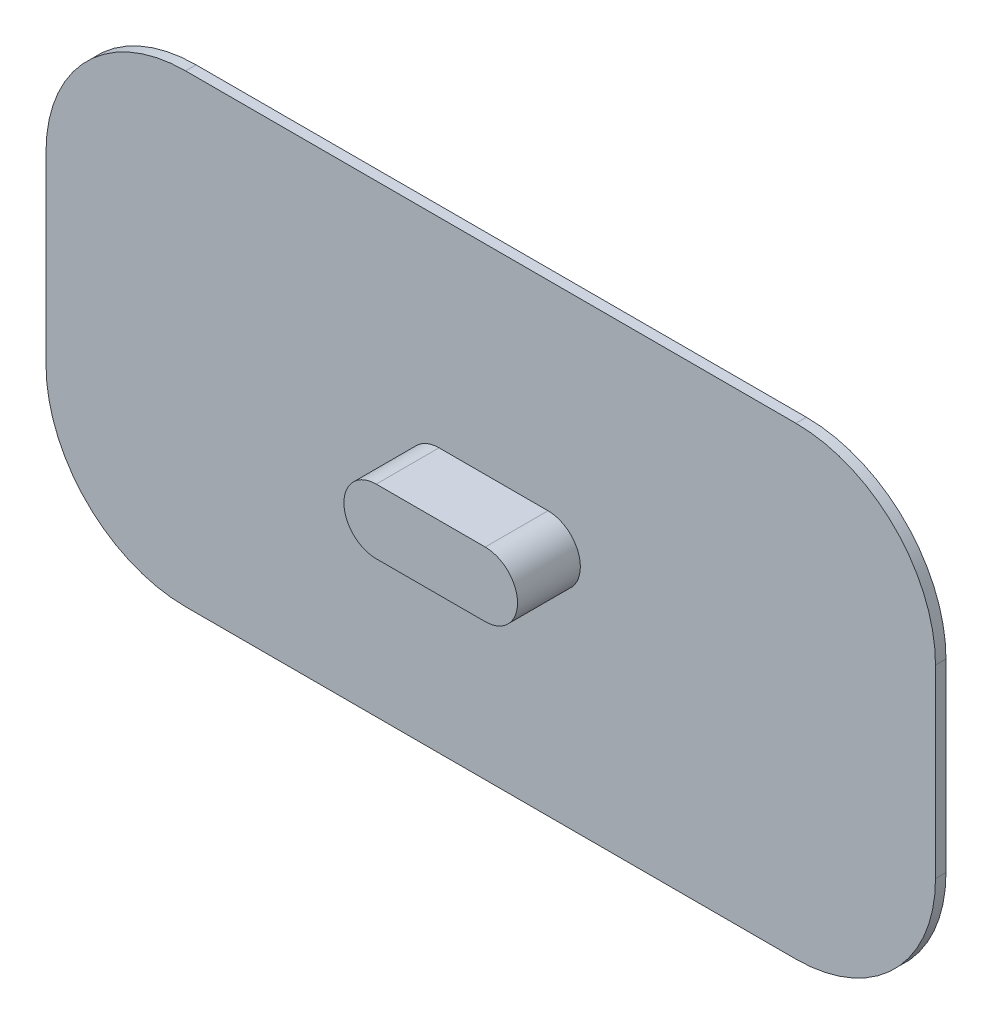
SolidWorks part; units mm, degrees
ref_plane "前视基准面" through (0, 0, 0) normal (0, 0, 1) x (1, 0, 0)
ref_plane "上视基准面" through (0, 0, 0) normal (0, 1, 0) x (1, 0, 0)
ref_plane "右视基准面" through (0, 0, 0) normal (1, 0, 0) x (0, 0, -1)
sketch "草图1" plane through (0, 0, 0) normal (0, 0, 1) x (1, 0, 0)
  line L8 (87.45, 66.5) -> (-87.45, 66.5)
  line L9 (-127.45, 26.5) -> (-127.45, -26.5)
  line L10 (-87.45, -66.5) -> (87.45, -66.5)
  line L11 (127.45, -26.5) -> (127.45, 26.5)
  arc A8 (-87.45, 66.5) -> (-127.45, 26.5) centre (-87.45, 26.5) ccw
  arc A9 (-127.45, -26.5) -> (-87.45, -66.5) centre (-87.45, -26.5) ccw
  arc A10 (87.45, -66.5) -> (127.45, -26.5) centre (87.45, -26.5) ccw
  arc A11 (127.45, 26.5) -> (87.45, 66.5) centre (87.45, 26.5) ccw
extrude "凸台-拉伸1" add sketch "草图1" along normal blind 3 contours A9 L10 A10 L11 A11 L8 A8 L9
sketch "草图2" plane through (0, 0, 3) normal (0, 0, 1) x (1, 0, 0)
  line L0 (-14.8218, 0) -> (16.4099, 0) construction
  line L1 (-14.8218, 9.2636) -> (16.4099, 9.2636)
  line L2 (-14.8218, -9.2636) -> (16.4099, -9.2636)
  arc A0 (-14.8218, 9.2636) -> (-14.8218, -9.2636) centre (-14.8218, 0) ccw
  arc A1 (16.4099, -9.2636) -> (16.4099, 9.2636) centre (16.4099, 0) ccw
  point P3 (0.794, 0)
extrude "凸台-拉伸2" add sketch "草图2" along normal blind 18
